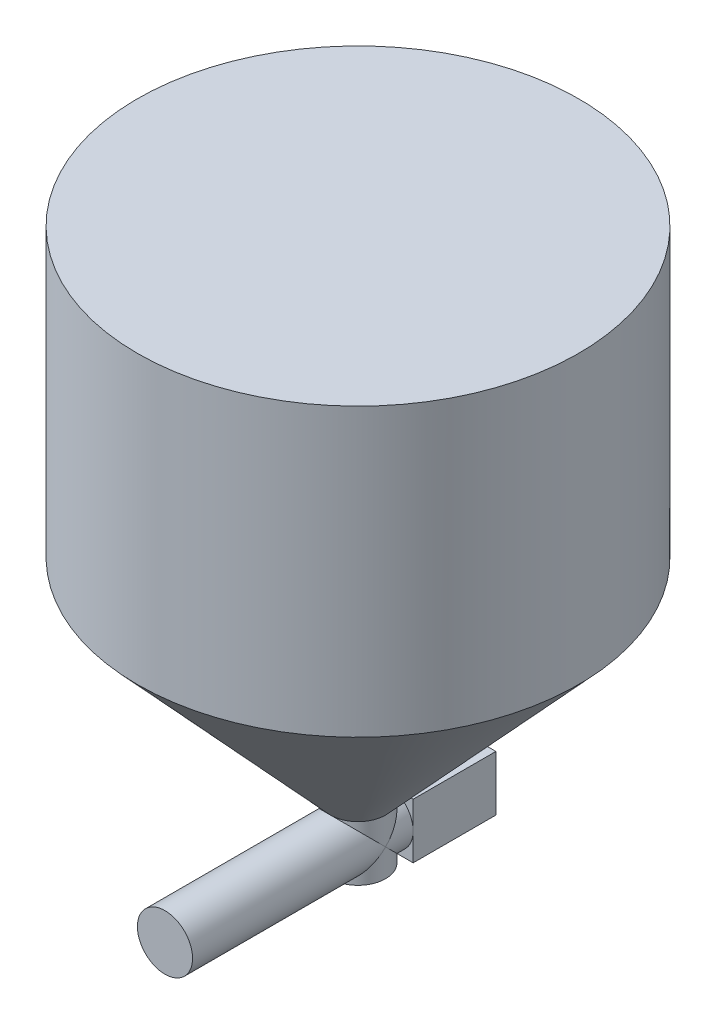
SolidWorks part; units mm, degrees
ref_plane "Alzado" through (0, 0, 0) normal (0, 0, 1) x (1, 0, 0)
ref_plane "Planta" through (0, 0, 0) normal (0, 1, 0) x (1, 0, 0)
ref_plane "Vista lateral" through (0, 0, 0) normal (1, 0, 0) x (0, 0, -1)
sketch "Croquis1" plane through (0, 0, 0) normal (0, 1, 0) x (1, 0, 0)
  circle A0 centre (0, 0) radius 400
  dimension "D1" = 800
ref_plane "Plano1" through (0, -900, 0) normal (0, 1, 0) x (1, 0, 0)
extrude "Saliente-Extruir1" add sketch "Croquis1" against normal blind 520 contours A0
sketch "Croquis2" plane through (0, -520, 0) normal (0, -1, 0) x (1, 0, 0)
  circle A0 centre (0, 0) radius 400
  dimension "D1" = 800
sketch "Croquis3" plane through (0, -900, 0) normal (0, 1, 0) x (1, 0, 0)
  circle A0 centre (0, 0) radius 50
  dimension "D1" = 100
loft "Recubrir1" add profiles "Croquis3", "Croquis2"
sketch "Croquis4" plane through (0, -900, 0) normal (0, -1, 0) x (1, 0, 0)
  circle A0 centre (0, 0) radius 50
extrude "Saliente-Extruir2" add sketch "Croquis4" along normal blind 100
ref_plane "Plano2" through (0, 0, -50) normal (0, 0, -1) x (-1, 0, 0)
sketch "Croquis5" plane through (0, 0, -50) normal (0, 0, -1) x (-1, 0, 0)
  line L0 (-50, -1000) -> (50, -1000) construction
  line L3 (0, -1000) -> (0, -900) construction
  line L4 (440, -900) -> (-440, -900) construction
  circle A0 centre (0, -950) radius 50
extrude "Saliente-Extruir3" add sketch "Croquis5" against normal blind 400
sketch "Croquis6" plane through (0, 0, -50) normal (0, 0, -1) x (-1, 0, 0)
  line L0 (50, -950) -> (-50, -950) construction
  line L2 (-50, -900) -> (50, -900)
  line L3 (-50, -900) -> (-50, -1000)
  line L4 (-50, -1000) -> (50, -1000)
  line L5 (50, -900) -> (50, -1000)
  line L6 (-50, -900) -> (50, -1000) construction
  line L7 (-50, -1000) -> (50, -900) construction
  circle A0 centre (0, -950) radius 50 construction
  circle A1 centre (0, -950) radius 50 construction
  point P8 (0, -950)
  dimension "D1" = 100
  dimension "D2" = 100
  dimension "D3" = 50
extrude "Saliente-Extruir4" add sketch "Croquis6" along normal blind 150
